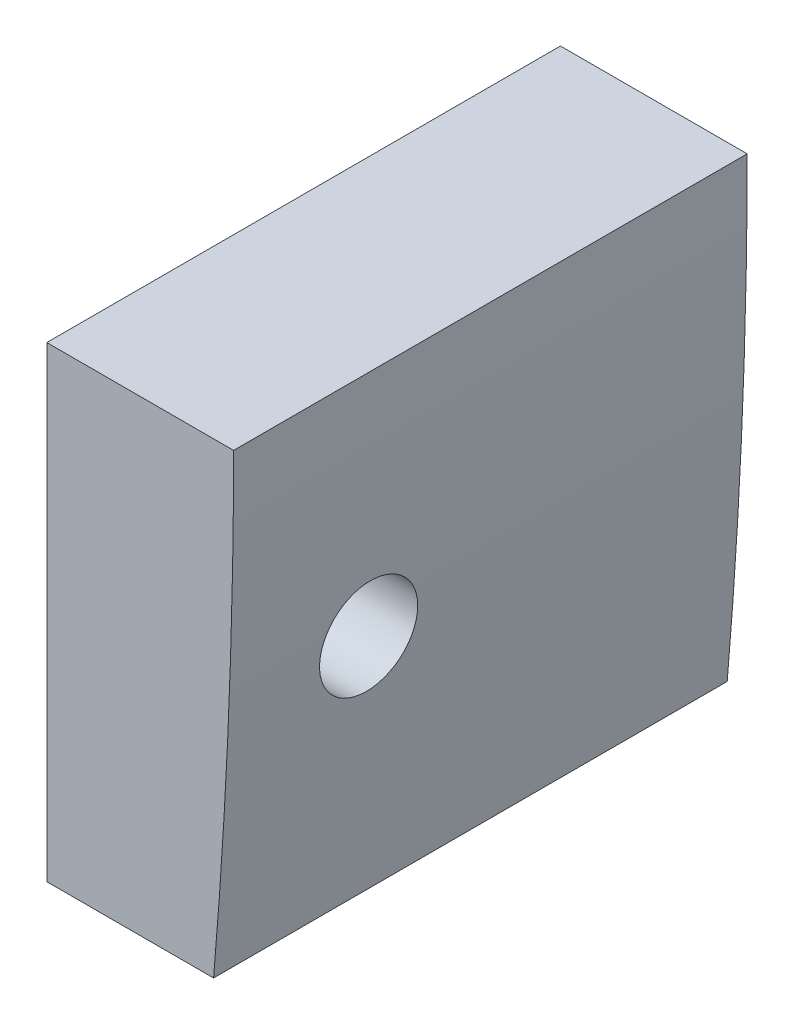
SolidWorks part; units mm, degrees
ref_plane "Front Plane" through (0, 0, 0) normal (0, 0, 1) x (1, 0, 0)
ref_plane "Top Plane" through (0, 0, 0) normal (0, 1, 0) x (1, 0, 0)
ref_plane "Right Plane" through (0, 0, 0) normal (1, 0, 0) x (0, 0, -1)
sketch "Sketch1" plane through (0, 0, 0) normal (0, 0, 1) x (1, 0, 0)
  line L1 (136.4169, 32.8301) -> (136.2499, 27.7383) construction
  line L4 (136.4811, 38.5741) -> (128.4811, 38.5741)
  line L5 (128.4811, 38.5741) -> (128.4811, 18.5741)
  line L7 (128.4811, 18.5741) -> (135.6252, 18.5741)
  line L9 (136.2499, 27.7383) -> (135.8632, 22.0659) construction
  line L10 (136.4607, 42.4419) -> (136.5009, 34.844) construction
  spline S0 degree 2 poles (136.4811, 38.5741) (136.4792, 28.5574) (135.6252, 18.5741) knots 0 0 0 1 1 1
  dimension "D1" = 20
  dimension "D2" = 8
extrude "Boss-Extrude1" add sketch "Sketch1" along normal blind 12 and the other way blind 10
sketch "Sketch2" plane through (128.4811, 0, 0) normal (-1, 0, 0) x (0, 0, 1)
  line L0 (-10, 38.5741) -> (-10, 18.5741) construction
  line L2 (12, 18.5741) -> (12, 38.5741) construction
  circle A0 centre (6, 28.5741) radius 2.1
  point P5 (-10, 28.5741)
  dimension "D1" = 4.2
  dimension "D2" = 6
extrude "Cut-Extrude1" cut sketch "Sketch2" against normal up to next from offset 2
